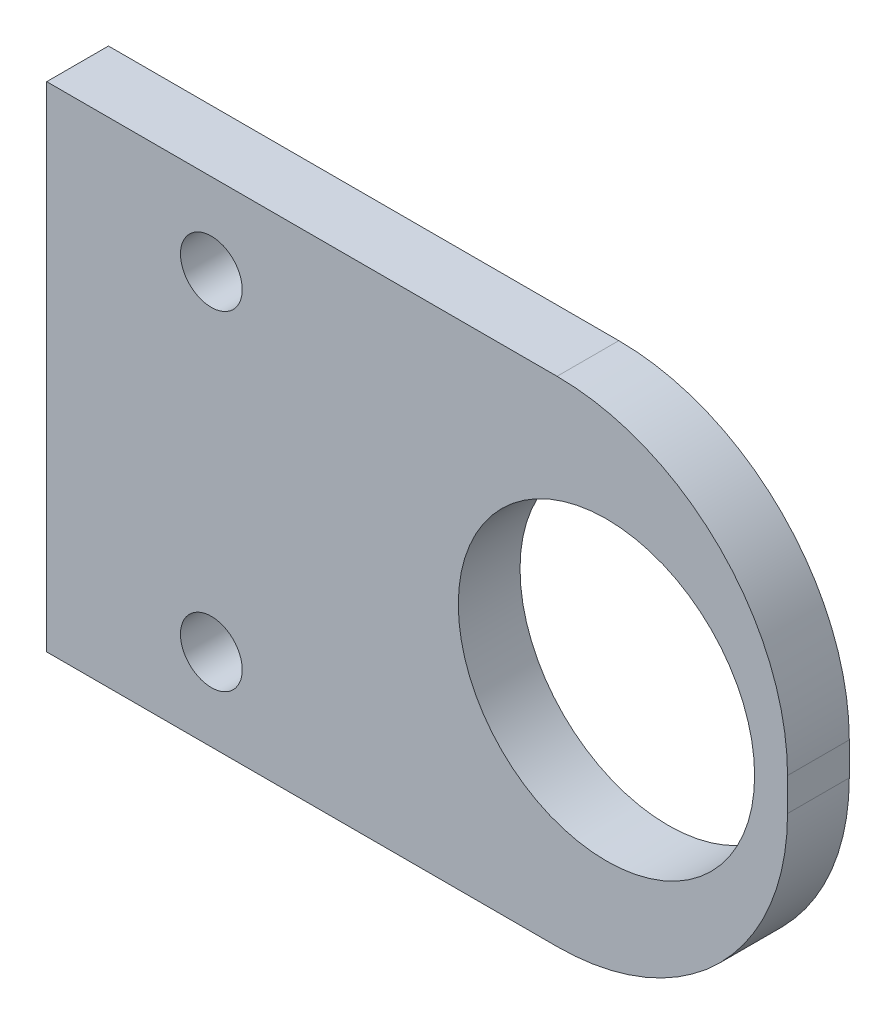
SolidWorks part; units mm, degrees
ref_plane "Front Plane" through (0, 0, 0) normal (0, 0, 1) x (1, 0, 0)
ref_plane "Top Plane" through (0, 0, 0) normal (0, 1, 0) x (1, 0, 0)
ref_plane "Right Plane" through (0, 0, 0) normal (1, 0, 0) x (0, 0, -1)
sketch "Sketch1" plane through (0, 0, 0) normal (0, 0, 1) x (1, 0, 0)
  line L1 (-28.575, 19.05) -> (10.795, 19.05)
  line L2 (-28.575, 19.05) -> (-28.575, -19.05)
  line L3 (-28.575, -19.05) -> (10.795, -19.05)
  line L4 (28.575, 1.27) -> (28.575, -1.27)
  line L5 (-28.575, 19.05) -> (28.575, -19.05) construction
  line L6 (-28.575, -19.05) -> (28.575, 19.05) construction
  circle A0 centre (14.605, 0) radius 11.43
  circle A1 centre (-15.875, 12.7) radius 2.3813
  circle A2 centre (-15.875, -12.7) radius 2.3813
  arc A3 (10.795, -19.05) -> (28.575, -1.27) centre (10.795, -1.27) ccw
  arc A4 (10.795, 19.05) -> (28.575, 1.27) centre (10.795, 1.27) cw
  point P0 (0, 0)
  dimension "D3" = 22.86
  dimension "D7" = 4.7625
  dimension "D8" = 4.7625
  dimension "D11" = 17.78
  dimension "D1" = 38.1
  dimension "D2" = 57.15
  dimension "D4" = 13.97
  dimension "D5" = 12.7
  dimension "D6" = 12.7
  dimension "D9" = 25.4
  dimension "D10" = 6.35
extrude "Boss-Extrude1" add sketch "Sketch1" along normal blind 4.7625
